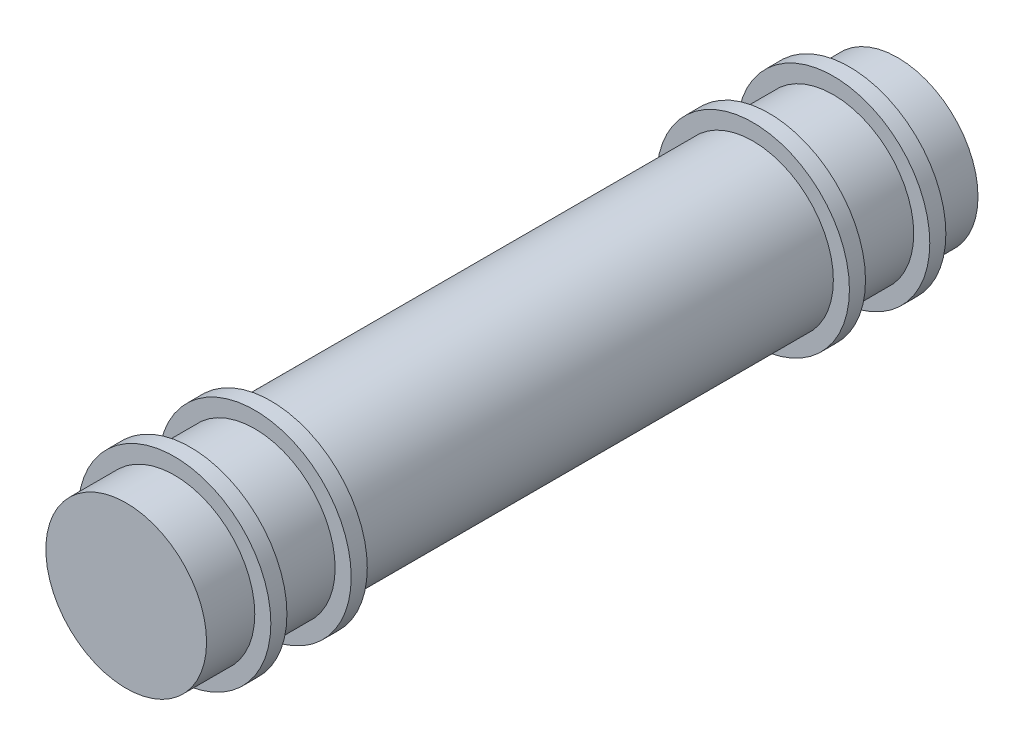
SolidWorks part; units mm, degrees
ref_plane "Plano frontal" through (0, 0, 0) normal (0, 0, 1) x (1, 0, 0)
ref_plane "Plano superior" through (0, 0, 0) normal (0, 1, 0) x (1, 0, 0)
ref_plane "Plano direito" through (0, 0, 0) normal (1, 0, 0) x (0, 0, -1)
sketch "Esboço1" plane through (0, 0, 0) normal (0, 0, 1) x (1, 0, 0)
  circle A0 centre (0, 0) radius 2.5
extrude "Ressalto-extrusão1" add sketch "Esboço1" along normal blind 24
sketch "Esboço2" plane through (0, 0, 0) normal (1, 0, 0) x (0, 0, -1)
  line L0 (-1.5, 0) -> (-1.5, -3)
  line L1 (-1.5, -3) -> (-2, -3)
  line L2 (-2, -3) -> (-2, 0)
  line L3 (-2, 0) -> (-1.5, 0)
  line L4 (-4, 0) -> (-4, -3)
  line L5 (-4, -3) -> (-4.5, -3)
  line L6 (-4.5, -3) -> (-4.5, 0)
  line L7 (-4.5, 0) -> (-4, 0)
  point P4 (0, 0)
  point P10 (0, 0)
  point P11 (0, 0)
  point P12 (0, 0)
  point P13 (0, 0)
  point P14 (0, 0)
  point P15 (0, 0)
  point P16 (0, 0)
  point P17 (0, 0)
  point P18 (0, 0)
  point P19 (0, 0)
revolve "Revolução1" add sketch "Esboço2" angle 360 about L3
sketch "Esboço4" plane through (0, 0, 0) normal (1, 0, 0) x (0, 0, -1)
  line L0 (-19.5, 0) -> (-19.5, -3)
  line L1 (-19.5, -3) -> (-20, -3)
  line L2 (-20, -3) -> (-20, 0)
  line L3 (-20, 0) -> (-19.5, 0)
  line L4 (-22.5, 0) -> (-22.5, -3)
  line L5 (-22.5, -3) -> (-22, -3)
  line L6 (-22, -3) -> (-22, 0)
  line L7 (-22, 0) -> (-22.5, 0)
  point P9 (0, 0)
  point P10 (0, 0)
  point P11 (0, 0)
  point P12 (0, 0)
  point P13 (0, 0)
  point P14 (0, 0)
  point P15 (0, 0)
  point P16 (0, 0)
  point P17 (0, 0)
  point P18 (0, 0)
revolve "Revolução2" add sketch "Esboço4" angle 360 about L3
